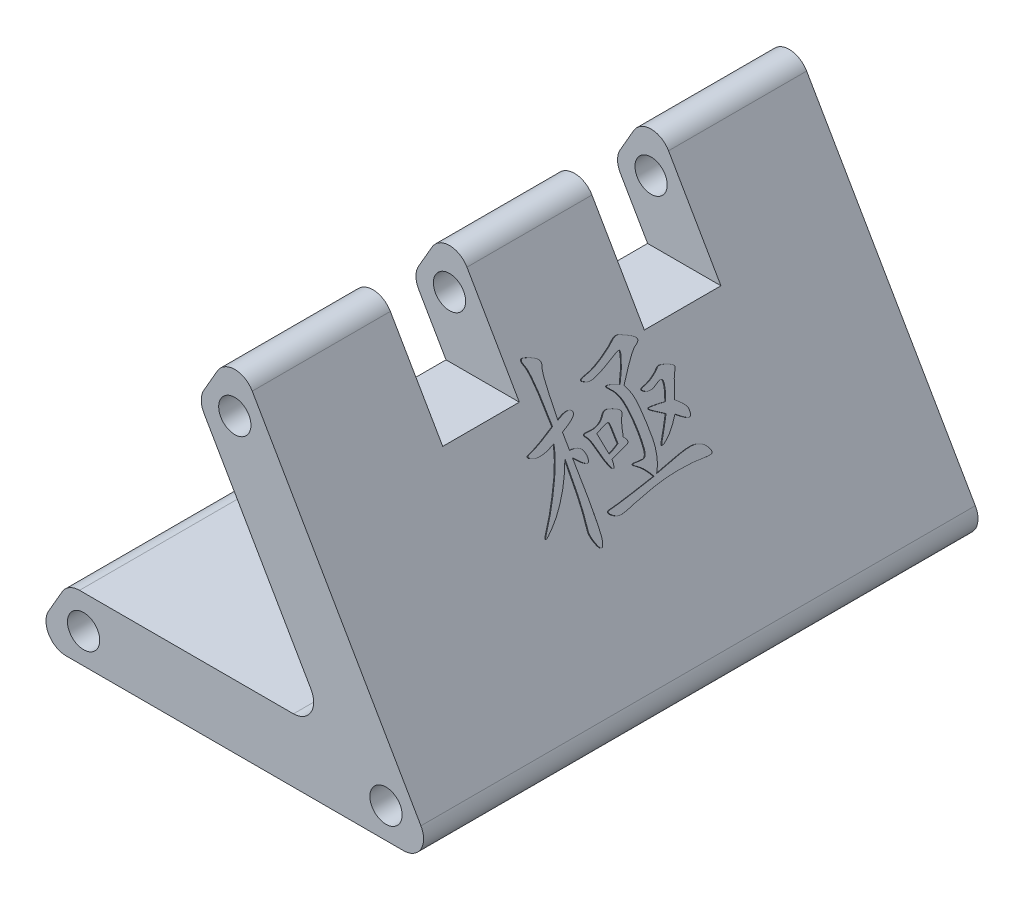
SolidWorks part; units mm, degrees
material "ABS"
ref_plane "前视基准面" through (0, 0, 0) normal (0, 0, 1) x (1, 0, 0)
ref_plane "上视基准面" through (0, 0, 0) normal (0, 1, 0) x (1, 0, 0)
ref_plane "右视基准面" through (0, 0, 0) normal (1, 0, 0) x (0, 0, -1)
sketch "草图1" plane through (0, 0, 0) normal (0, 0, 1) x (1, 0, 0)
  line L0 (0, 0) -> (-15, -25.9808) construction
  line L1 (-15, -25.9808) -> (15, -25.9808) construction
  line L2 (15, -25.9808) -> (0, 0) construction
  line L3 (20.1962, -28.9808) -> (0, 6)
  line L4 (0, 6) -> (-20.1962, -28.9808)
  line L5 (-20.1962, -28.9808) -> (20.1962, -28.9808)
  circle A0 centre (0, 0) radius 1.6
  circle A1 centre (-15, -25.9808) radius 1.6
  circle A2 centre (15, -25.9808) radius 1.6
  dimension "D3" = 3.2
  dimension "D1" = 30
  dimension "D2" = 3
extrude "凸台-拉伸1" add sketch "草图1" along normal mid plane 55
fillet "圆角1" radius 2 3 edges at (20.1962, -28.9808, 0) (-20.1962, -28.9808, 0) (0, 6, 0)
sketch "草图2" plane through (0, 0, -27.5) normal (0, 0, -1) x (-1, 0, 0)
  line L0 (3.6373, -0.3) -> (-9.2842, -22.6808)
  line L1 (1.7321, 3) -> (18.4641, -25.9808) construction
  line L2 (-9.2842, -22.6808) -> (16.5588, -22.6808)
  line L3 (16.5588, -22.6808) -> (3.6373, -0.3)
  line L4 (0, 0) -> (-15, -25.9808) construction
  circle A0 centre (15, -25.9808) radius 1.6 construction
  dimension "D1" = 3.3
  dimension "D2" = 3.3
extrude "切除-拉伸1" cut sketch "草图2" against normal mid plane 133
fillet "圆角2" radius 2 3 edges at (-16.5588, -22.6808, 0) (9.2842, -22.6808, 0) (-3.6373, -0.3, 0)
sketch "草图3" plane through (2.5981, 1.5, 0) normal (0.866, 0.5, 0) x (0, 0, -1)
  line L0 (-27.5, -19.7321) -> (27.5, -19.7321) construction
  line L1 (-27.5, -31.7321) -> (-27.5, 1.7321) construction
  line L2 (27.5, -31.7321) -> (27.5, 1.7321) construction
  line L3 (-27.5, -31.7321) -> (27.5, -31.7321) construction
  text T0 "極" font "楷体" height 12
  dimension "D1" = 12
extrude "凸台-拉伸2" add sketch "草图3" along normal mid plane 0.2
sketch "草图4" plane through (0, 0, 0) normal (1, 0, 0) x (0, 0, -1)
  line L0 (27.5, 4) -> (-27.5, 4) construction
  line L1 (-13.8, -6) -> (-6.2, -6)
  line L2 (-13.8, -6) -> (-13.8, 14)
  line L3 (-13.8, 14) -> (-6.2, 14)
  line L4 (-6.2, -6) -> (-6.2, 14)
  line L5 (-10, 14) -> (-10, -6) construction
  line L6 (-13.8, 4) -> (-6.2, 4) construction
  line L7 (0, 0) -> (0, 9.2299) construction
  line L8 (13.8, 4) -> (6.2, 4) construction
  line L9 (10, 14) -> (10, -6) construction
  line L10 (6.2, -6) -> (6.2, 14)
  line L11 (13.8, 14) -> (6.2, 14)
  line L12 (13.8, -6) -> (13.8, 14)
  line L13 (13.8, -6) -> (6.2, -6)
  point P0 (-10, 4)
  point P16 (10, 4)
  point P17 (0, 0)
  point P18 (0, 0)
  point P19 (0, 0)
  point P20 (0, 9.2299)
  dimension "D1" = 7.6
  dimension "D2" = 20
  dimension "D3" = 10
extrude "切除-拉伸2" cut sketch "草图4" against normal mid plane 50
